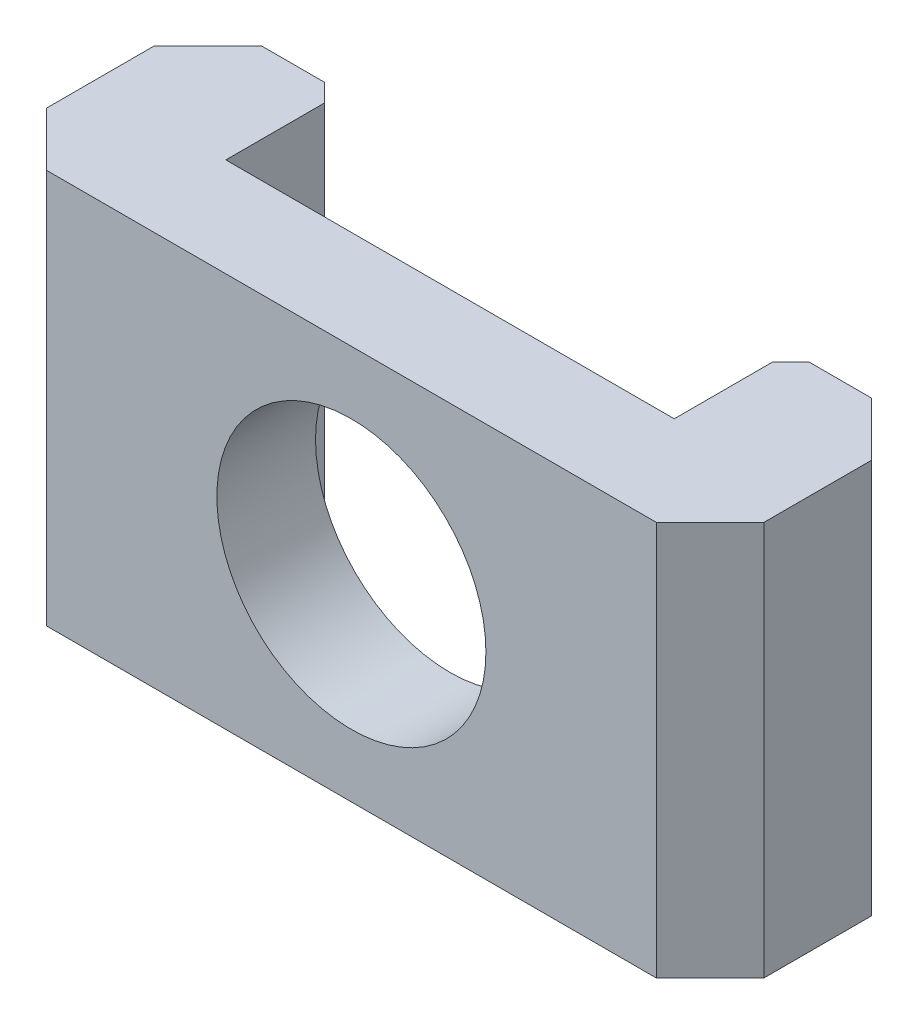
SolidWorks part; units mm, degrees
material "Q235A"
ref_plane "前视基准面" through (0, 0, 0) normal (0, 0, 1) x (1, 0, 0)
ref_plane "上视基准面" through (0, 0, 0) normal (0, 1, 0) x (1, 0, 0)
ref_plane "右视基准面" through (0, 0, 0) normal (1, 0, 0) x (0, 0, -1)
sketch "草图1" plane through (0, 0, 0) normal (0, 0, 1) x (1, 0, 0)
  line L0 (0, 11) -> (0, -11) construction
  line L1 (-20, 11) -> (20, 11)
  line L2 (-20, 11) -> (-20, -11)
  line L3 (-20, -11) -> (20, -11)
  line L4 (20, 11) -> (20, -11)
  dimension "D1" = 40
  dimension "D2" = 22
extrude "拉伸1" add sketch "草图1" along normal mid plane 12
sketch "草图3" plane through (0, -11, 0) normal (0, -1, 0) x (1, 0, 0)
  line L0 (-16.5, 3.5) -> (16.5, 3.5) construction
  line L1 (0, 0) -> (0, 3.5) construction
  line L2 (-20, 6) -> (20, 6) construction
  dimension "D1" = 33
  dimension "D2" = 2.5
hole_wizard "M3 Tapped Hole1" positions "3D草图1" profile "草图4" tap size "M3" standard "GB"
sketch3d "3D草图1"
  point P0 (-16.5, -11, 3.5)
  point P3 (16.5, -11, 3.5)
sketch "草图4" plane through (-16.5, -11, 3.5) normal (1, 0, 0) x (0, 0, -1)
  line L0 (0, 0) -> (0, 10.2511)
  line L1 (0, 10.2511) -> (1.25, 9.5)
  line L2 (1.25, 9.5) -> (1.25, 0)
  line L5 (1.25, 0) -> (0, 0)
  line L10 (0, 10.2511) -> (-1.25, 9.5) construction
  line L11 (0, -6.35) -> (0, 107.95) construction
  dimension "螺纹孔钻头直径" = 2.5
  dimension "螺纹孔钻头深度" = 9.5
  dimension "导头角度" = 118
cosmetic thread "孔螺蚊线1" parameters "D1"=8, "D2"=3
cosmetic thread "孔螺蚊线2" parameters "D1"=8, "D2"=3
chamfer "倒角1" distance 0.5 angle 45 2 edges at (16.5, -11, 2.25) (-16.5, -11, 2.25)
sketch "草图5" plane through (0, 0, 6) normal (0, 0, 1) x (1, 0, 0)
  line L1 (-20, -11) -> (20, -11) construction
  line L5 (0, -11) -> (0, 0) construction
  circle A0 centre (0, 0) radius 7.5
  dimension "D1" = 15
  dimension "D2" = 11
extrude "拉伸2" cut sketch "草图5" against normal up to surface (12 mm away) up to face at (0, 0, -6)
chamfer "倒角2" [suppressed] distance 1 angle 45
sketch "草图6" plane through (0, -11, 0) normal (0, -1, 0) x (1, 0, 0)
  line L0 (-8, 3.5) -> (8, 3.5)
  line L1 (0, 0) -> (0, 3.5)
  line L2 (-20, 6) -> (20, 6) construction
  dimension "D1" = 16
  dimension "D2" = 2.5
hole_wizard "M3 Tapped Hole2" [suppressed] positions "3D草图2" profile "草图7" tap size "M3" standard "GB"
sketch3d "3D草图2"
  point P7 (0, -11, 3.5)
sketch "草图7" plane through (0, -11, 3.5) normal (1, 0, 0) x (0, 0, -1)
  line L0 (0, 0) -> (0, 10.2511)
  line L1 (0, 10.2511) -> (1.25, 9.5)
  line L2 (1.25, 9.5) -> (1.25, 0)
  line L5 (1.25, 0) -> (0, 0)
  line L10 (0, 10.2511) -> (-1.25, 9.5) construction
  line L11 (0, -6.35) -> (0, 107.95) construction
  dimension "螺纹孔钻头直径" = 2.5
  dimension "螺纹孔钻头深度" = 9.5
  dimension "导头角度" = 118
cosmetic thread "孔螺蚊线3" [suppressed] parameters "D1"=3.6049, "D2"=3
chamfer "倒角3" [suppressed] distance 0.5 angle 45
mirror "Mirror1" about plane through (0, 0, 0) normal (0, 0, 1) of "M3 Tapped Hole1"
chamfer "Chamfer1" distance 0.5 angle 45 2 edges at (16.5, -11, -4.75) (-16.5, -11, -4.75)
sketch "Sketch1" plane through (0, 0, -6) normal (0, 0, 1) x (1, 0, 0)
  circle A0 centre (0, 0) radius 10
  dimension "D1" = 20
extrude "Extrude1" [suppressed] cut sketch "Sketch1" along normal blind 6
sketch "Sketch2" plane through (0, 0, -6) normal (0, 0, -1) x (-1, 0, 0)
  line L0 (-20, 11) -> (20, 11) construction
  line L1 (-12.5, 11) -> (12.5, 11)
  line L2 (-12.5, 11) -> (-12.5, -11)
  line L3 (-12.5, -11) -> (12.5, -11)
  line L4 (12.5, 11) -> (12.5, -11)
  line L5 (20, -11) -> (-20, -11) construction
  line L6 (0, 0) -> (0, 11) construction
  dimension "D1" = 25
extrude "Extrude2" cut sketch "Sketch2" against normal blind 6.5
chamfer "Chamfer2" distance 1 angle 45 2 edges at (-12.5, 0, -6) (12.5, 0, -6)
chamfer "Chamfer3" distance 3 angle 45 4 edges at (20, 0, -6) (20, 0, 6) (-20, 0, 6) (-20, 0, -6)
